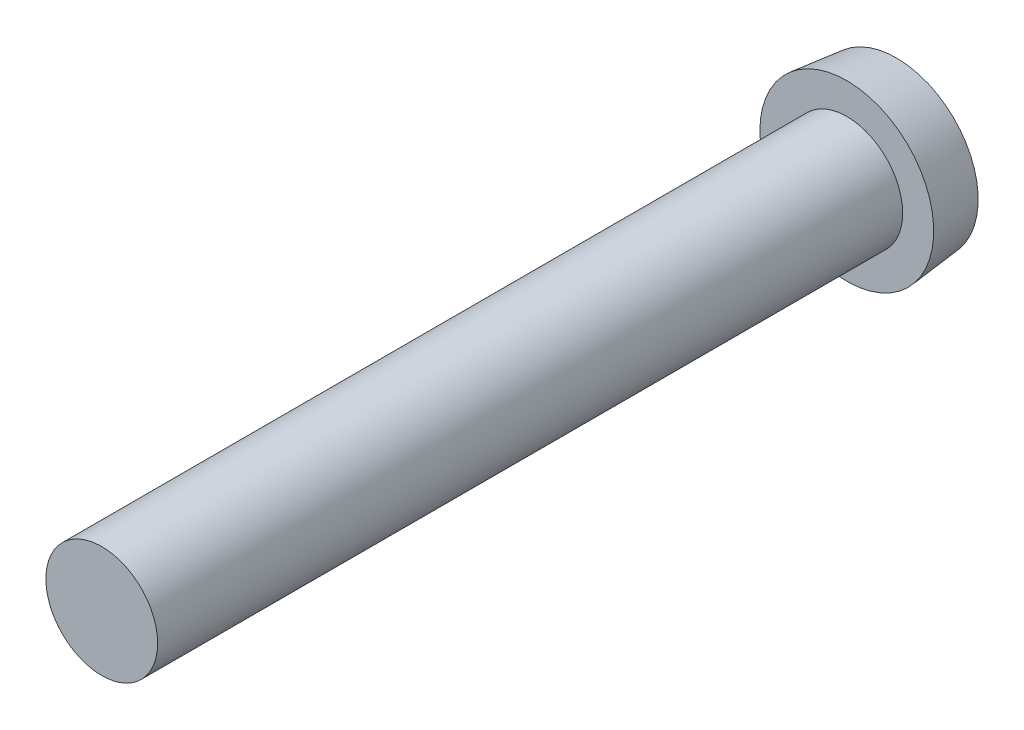
SolidWorks part; units mm, degrees
ref_plane "Front Plane" through (0, 0, 0) normal (0, 0, 1) x (1, 0, 0)
ref_plane "Top Plane" through (0, 0, 0) normal (0, 1, 0) x (1, 0, 0)
ref_plane "Right Plane" through (0, 0, 0) normal (1, 0, 0) x (0, 0, -1)
sketch "Sketch1" plane through (0, 0, 0) normal (0, 0, 1) x (1, 0, 0)
  circle A0 centre (0, 0) radius 2.25
  dimension "D1" = 4.5
extrude "Boss-Extrude1" add sketch "Sketch1" along normal blind 30
sketch "Sketch2" plane through (0, 0, 0) normal (0, 0, -1) x (-1, 0, 0)
  circle A0 centre (0, 0) radius 3.5
  dimension "D1" = 7
extrude "Boss-Extrude2" add sketch "Sketch2" along normal blind 2 draft 6
sketch "Sketch3" plane through (0, 0, -2) normal (0, 0, -1) x (-1, 0, 0)
  line L0 (-0.4, 0.4) -> (-0.4, 3.0654)
  line L1 (0.2, -3.2654) -> (-0.2, -3.2654)
  line L2 (0.4, -3.0654) -> (0.4, -0.4)
  line L3 (0.2, 3.2654) -> (-0.2, 3.2654)
  line L4 (-0.4, -3.0654) -> (-0.4, -0.4)
  line L5 (0.4, -3.2654) -> (0.3849, -3.1417) construction
  line L6 (0.4, 3.2654) -> (0.049, 0.4) construction
  line L7 (-1.722, 0.4) -> (-0.4, 0.4)
  line L8 (-1.922, 0.2) -> (-1.922, -0.2)
  line L9 (-1.722, -0.4) -> (-0.4, -0.4)
  line L10 (1.922, 0.2) -> (1.922, -0.2)
  line L11 (-1.922, 0.4) -> (0.4, -0.0832) construction
  line L12 (-1.922, -0.4) -> (-0.4, -0.0832) construction
  line L13 (0.4, 0.4) -> (1.722, 0.4)
  line L14 (-0.3849, -3.1417) -> (-0.4, -3.2654) construction
  line L15 (0.4, 0.4) -> (0.4, 3.0654)
  line L16 (1.8141, 0.3775) -> (1.922, 0.4) construction
  line L17 (1.8141, -0.3775) -> (1.922, -0.4) construction
  line L18 (0, 0) -> (-0.4, 3.2654) construction
  line L20 (0, 0) -> (0.4, 0.0832) construction
  line L21 (0.4, -0.4) -> (1.722, -0.4)
  circle A0 centre (0, 0) radius 3.2898 construction
  arc A1 (-1.922, -0.2) -> (-1.722, -0.4) centre (-1.722, -0.2) ccw
  arc A2 (-1.722, 0.4) -> (-1.922, 0.2) centre (-1.722, 0.2) ccw
  arc A3 (1.922, -0.2) -> (1.722, -0.4) centre (1.722, -0.2) cw
  arc A4 (1.922, 0.2) -> (1.722, 0.4) centre (1.722, 0.2) ccw
  arc A5 (-0.2, -3.2654) -> (-0.4, -3.0654) centre (-0.2, -3.0654) cw
  arc A6 (0.4, -3.0654) -> (0.2, -3.2654) centre (0.2, -3.0654) cw
  arc A7 (0.4, 3.0654) -> (0.2, 3.2654) centre (0.2, 3.0654) ccw
  arc A8 (-0.2, 3.2654) -> (-0.4, 3.0654) centre (-0.2, 3.0654) ccw
  point P0 (0, 0)
  point P8 (0, 0)
  dimension "D3" = 0.2
  dimension "D1" = 0.8
  dimension "D2" = 0.8
extrude "Cut-Extrude1" cut sketch "Sketch3" against normal blind 1
